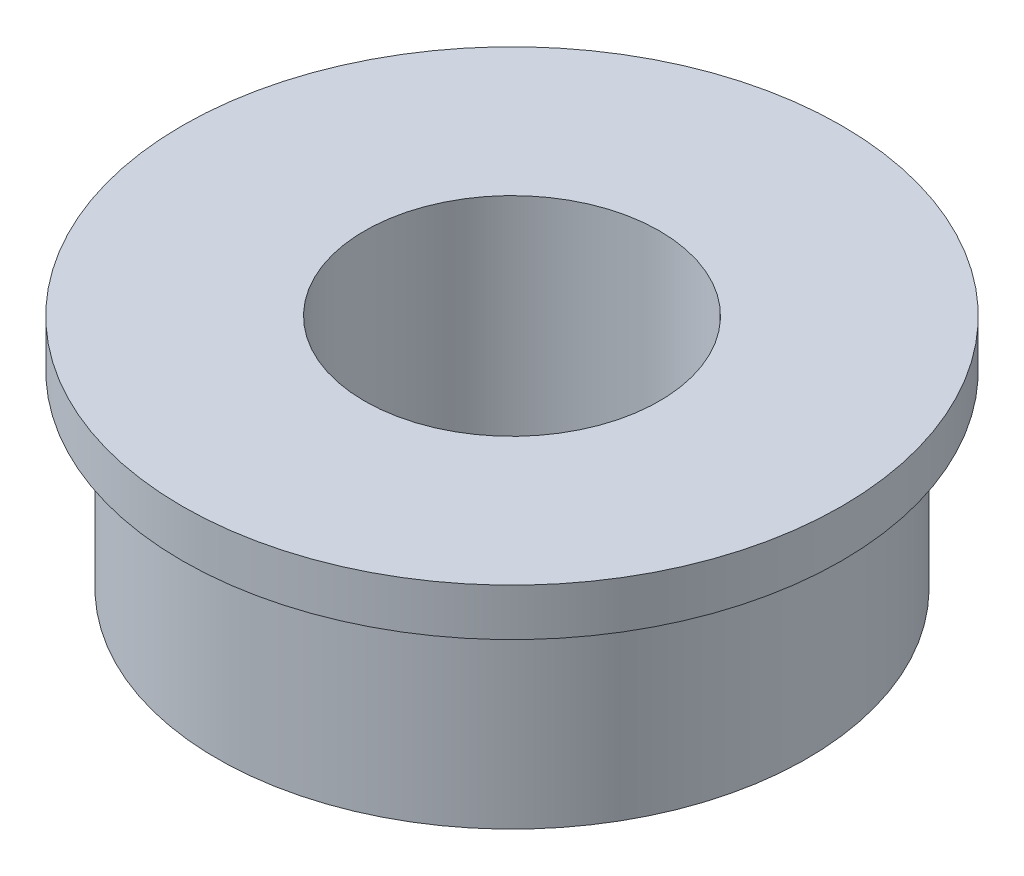
SolidWorks part; units mm, degrees
ref_plane "Piano frontale" through (0, 0, 0) normal (0, 0, 1) x (1, 0, 0)
ref_plane "Piano superiore" through (0, 0, 0) normal (0, 1, 0) x (1, 0, 0)
ref_plane "Piano destro" through (0, 0, 0) normal (1, 0, 0) x (0, 0, -1)
sketch "Schizzo1" plane through (0, 0, 0) normal (0, 0, 1) x (1, 0, 0)
  line L0 (0, 0) -> (0, 18.5042) construction
  line L1 (2.5, 4) -> (2.5, 0)
  line L2 (2.5, 0) -> (5, 0)
  line L3 (5, 0) -> (5, 3.2)
  line L4 (5, 3.2) -> (5.59, 3.2)
  line L5 (5.59, 3.2) -> (5.59, 4)
  line L6 (5.59, 4) -> (2.5, 4)
  dimension "D1" = 10
  dimension "D2" = 0.8
  dimension "D3" = 5
  dimension "D4" = 4
  dimension "D5" = 11.18
revolve "Rivoluzione1" add sketch "Schizzo1" angle 360 about L0
